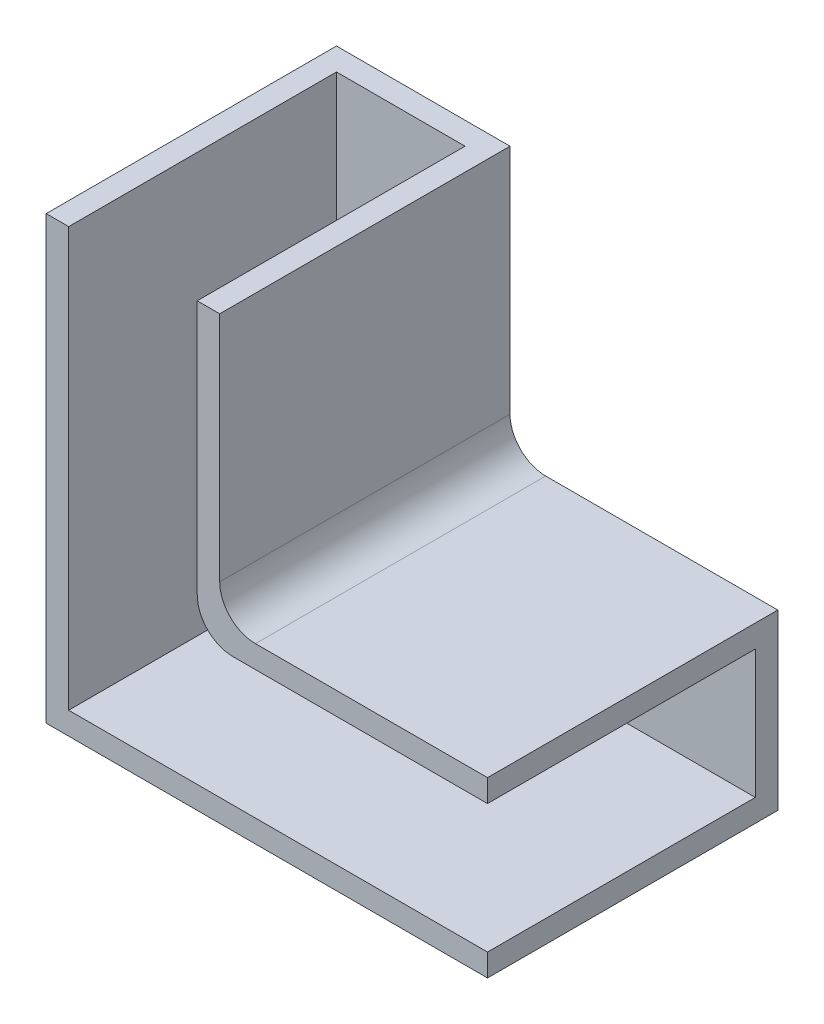
SolidWorks part; units mm, degrees
ref_plane "Front" through (0, 0, 0) normal (0, 0, 1) x (1, 0, 0)
ref_plane "Top" through (0, 0, 0) normal (0, 1, 0) x (1, 0, 0)
ref_plane "Right" through (0, 0, 0) normal (1, 0, 0) x (0, 0, -1)
sketch "Sketch1" plane through (0, 0, 0) normal (0, 0, 1) x (1, 0, 0)
  line L0 (0, 0) -> (0, 15.697)
  line L1 (0, 15.697) -> (6.172, 15.697)
  line L2 (6.172, 15.697) -> (6.172, 6.172)
  line L3 (6.172, 6.172) -> (15.697, 6.172)
  line L4 (15.697, 6.172) -> (15.697, 0)
  line L5 (0, 0) -> (15.697, 0)
  dimension "D1" = 6.172
  dimension "D2" = 6.172
  dimension "D3" = 9.525
  dimension "D4" = 9.525
extrude "Boss-Extrude1" add sketch "Sketch1" along normal blind 0.8
sketch "Sketch2" plane through (0, 0, 0.8) normal (0, 0, 1) x (1, 0, 0)
  line L6 (15.697, 0) -> (15.697, 6.172) construction
  line L7 (6.172, 15.697) -> (0, 15.697) construction
  line L12 (0.8, 0.8) -> (14.897, 0.8)
  line L13 (14.897, 0.8) -> (14.897, 5.372)
  line L14 (14.897, 5.372) -> (5.372, 5.372)
  line L15 (5.372, 5.372) -> (5.372, 14.897)
  line L16 (5.372, 14.897) -> (0.8, 14.897)
  line L17 (0.8, 14.897) -> (0.8, 0.8)
  line L18 (0.8, 0.8) -> (15.697, 0.8)
  line L20 (15.697, 5.372) -> (5.372, 5.372)
  line L21 (5.372, 5.372) -> (5.372, 15.697)
  line L23 (0.8, 15.697) -> (0.8, 0.8)
  line L24 (0.8, 15.697) -> (0, 15.697)
  line L25 (5.372, 15.697) -> (6.172, 15.697)
  line L26 (15.697, 6.172) -> (15.697, 5.372)
  line L27 (15.697, 0.8) -> (15.697, 0)
  line L30 (0, 0) -> (15.697, 0)
  line L31 (15.697, 0) -> (15.697, 6.172)
  line L32 (15.697, 6.172) -> (6.172, 6.172)
  line L33 (6.172, 6.172) -> (6.172, 15.697)
  line L34 (6.172, 15.697) -> (0, 15.697)
  line L35 (0, 15.697) -> (0, 0)
  line L36 (0, 0) -> (15.697, 0)
  line L38 (15.697, 6.172) -> (6.172, 6.172)
  line L39 (6.172, 6.172) -> (6.172, 15.697)
  line L41 (0, 15.697) -> (0, 0)
  dimension "D1" = 0.8
  dimension "D2" = 0
extrude "Boss-Extrude2" add sketch "Sketch2" along normal blind 9.525
fillet "Fillet1" radius 1.27 2 edges at (6.172, 6.172, 5.1625) (5.372, 5.372, 5.5625)
